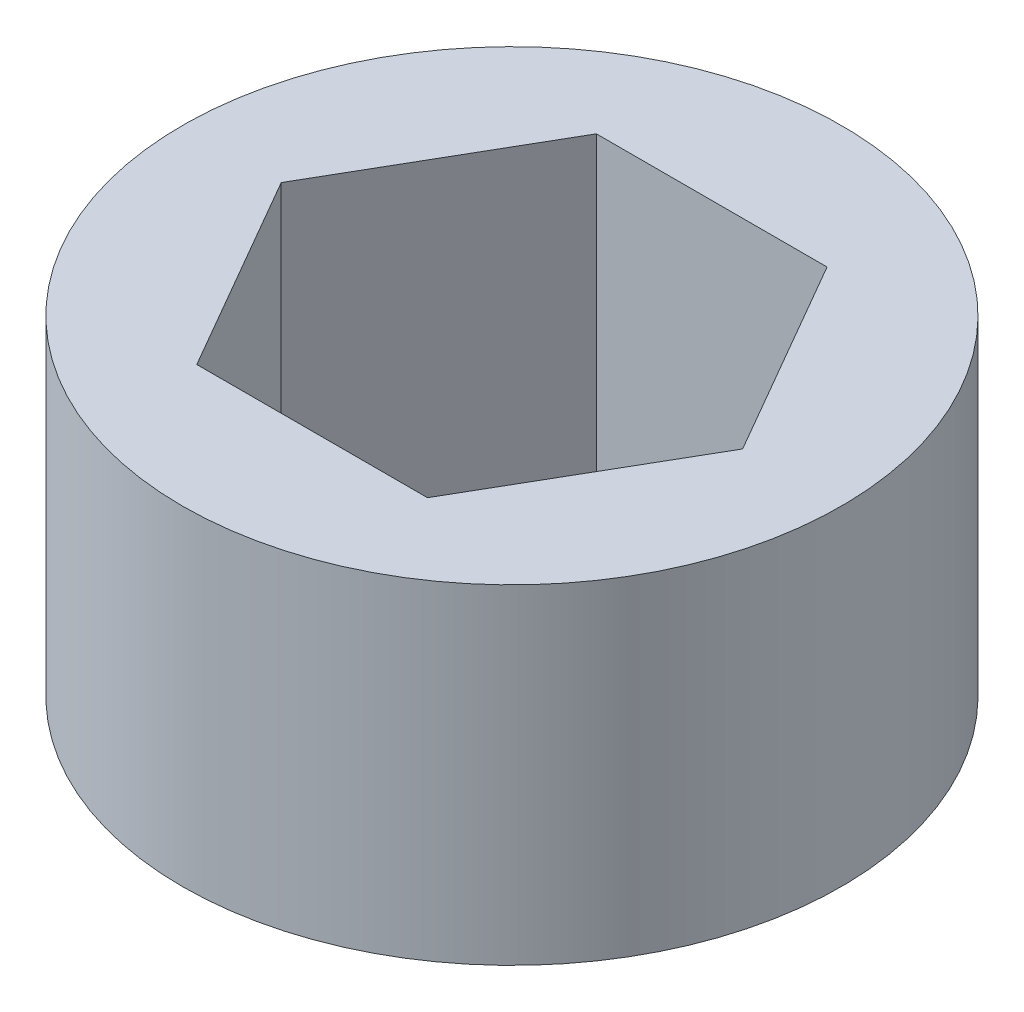
SolidWorks part; units mm, degrees
ref_plane "Front Plane" through (0, 0, 0) normal (0, 0, 1) x (1, 0, 0)
ref_plane "Top Plane" through (0, 0, 0) normal (0, 1, 0) x (1, 0, 0)
ref_plane "Right Plane" through (0, 0, 0) normal (1, 0, 0) x (0, 0, -1)
sketch "Sketch1" plane through (0, 0, 0) normal (0, 1, 0) x (1, 0, 0)
  circle A0 centre (0, 0) radius 6.35
  dimension "D1" = 12.7
extrude "Boss-Extrude1" add sketch "Sketch1" against normal blind 6.35
sketch "Sketch2" plane through (0, 0, 0) normal (0, 1, 0) x (1, 0, 0)
  line L1 (2.2225, 3.8495) -> (-2.2225, 3.8495)
  line L2 (-2.2225, 3.8495) -> (-4.445, 0)
  line L3 (-4.445, 0) -> (-2.2225, -3.8495)
  line L4 (-2.2225, -3.8495) -> (2.2225, -3.8495)
  line L5 (2.2225, -3.8495) -> (4.445, 0)
  line L6 (4.445, 0) -> (2.2225, 3.8495)
  circle A0 centre (0, 0) radius 3.8495 construction
  dimension "D1" = 8.89
extrude "Cut-Extrude1" cut sketch "Sketch2" against normal through all
